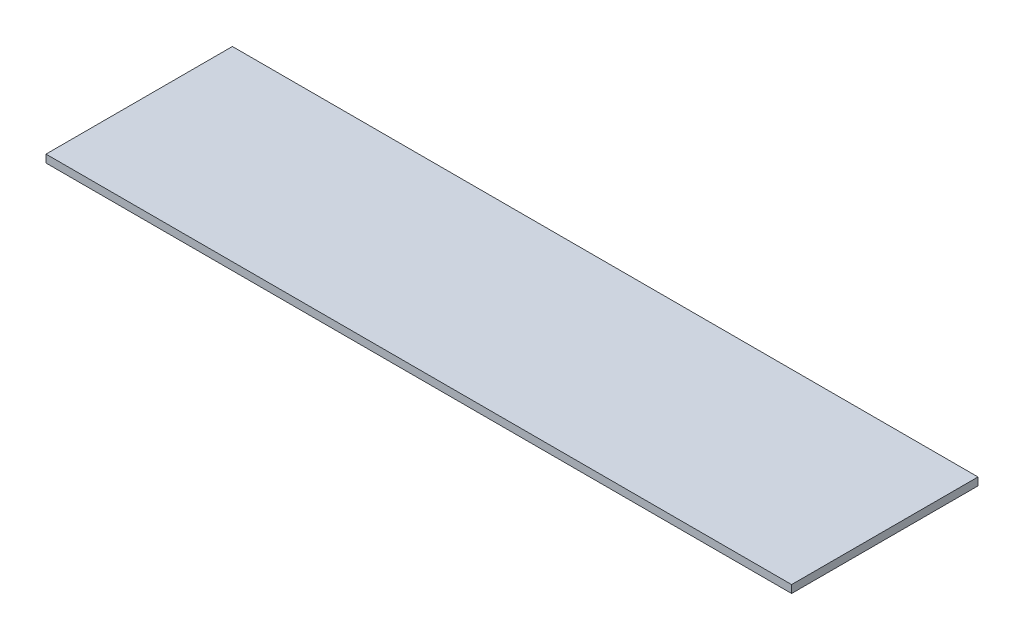
SolidWorks part; units mm, degrees
ref_plane "Front Plane" through (0, 0, 0) normal (0, 0, 1) x (1, 0, 0)
ref_plane "Top Plane" through (0, 0, 0) normal (0, 1, 0) x (1, 0, 0)
ref_plane "Right Plane" through (0, 0, 0) normal (1, 0, 0) x (0, 0, -1)
sketch "Sketch1" plane through (0, 0, 0) normal (0, 1, 0) x (1, 0, 0)
  line L1 (-304.8, 76.2) -> (304.8, 76.2)
  line L2 (-304.8, 76.2) -> (-304.8, -76.2)
  line L3 (-304.8, -76.2) -> (304.8, -76.2)
  line L4 (304.8, 76.2) -> (304.8, -76.2)
  line L5 (-304.8, 76.2) -> (304.8, -76.2) construction
  line L6 (-304.8, -76.2) -> (304.8, 76.2) construction
  point P0 (0, 0)
  dimension "D1" = 609.6
  dimension "D2" = 152.4
extrude "Boss-Extrude1" add sketch "Sketch1" along normal blind 6.35
